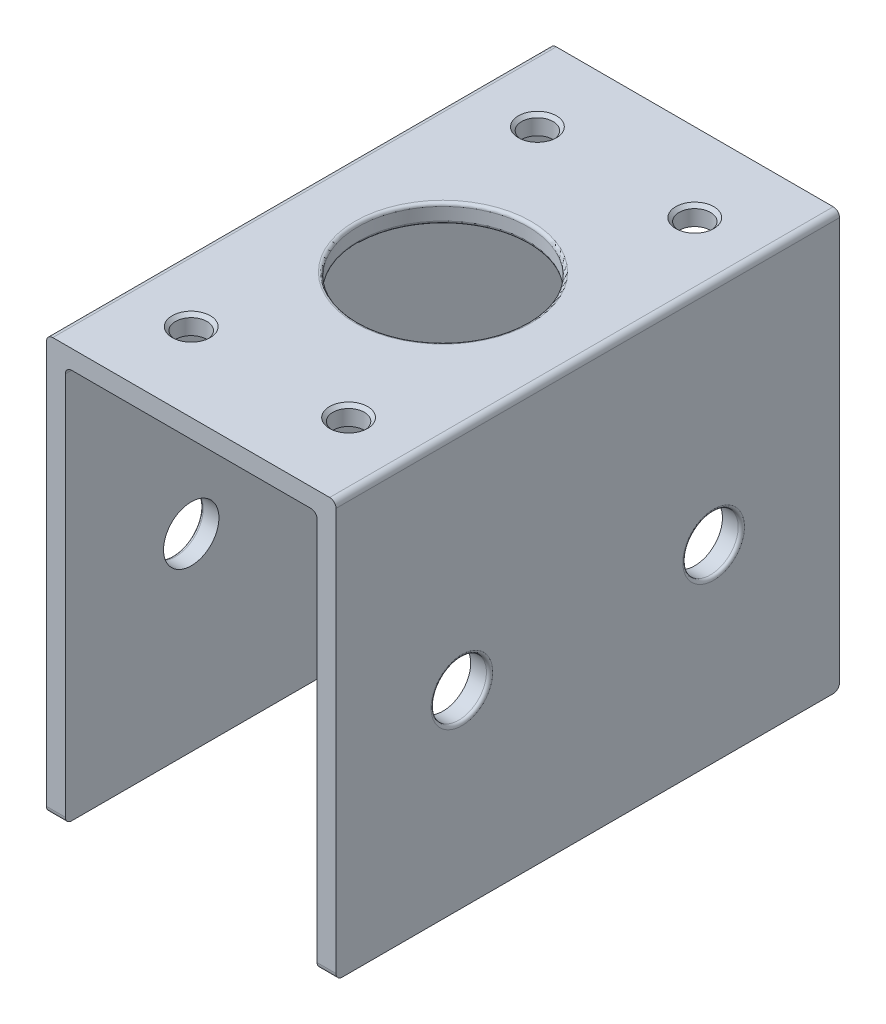
SolidWorks part; units mm, degrees
ref_plane "前视基准面" through (0, 0, 0) normal (0, 0, 1) x (1, 0, 0)
ref_plane "上视基准面" through (0, 0, 0) normal (0, 1, 0) x (1, 0, 0)
ref_plane "右视基准面" through (0, 0, 0) normal (1, 0, 0) x (0, 0, -1)
other "Configuration Table"
sketch "草图1" plane through (0, 0, 0) normal (0, 0, 1) x (1, 0, 0)
  line L0 (0, 0) -> (40, 0)
  line L1 (40, 0) -> (40, -63)
  line L2 (40, -63) -> (43, -63)
  line L3 (43, -63) -> (43, 3)
  line L4 (43, 3) -> (-3, 3)
  line L5 (-3, 3) -> (-3, -63)
  line L6 (-3, -63) -> (0, -63)
  line L7 (0, -63) -> (0, 0)
  dimension "D1" = 40
  dimension "D2" = 63
  dimension "D3" = 3
  dimension "D4" = 3
  dimension "D5" = 3
  dimension "D6" = 63
extrude "凸台-拉伸1" add sketch "草图1" along normal blind 80
sketch "草图2" plane through (0, 3, 0) normal (0, 1, 0) x (1, 0, 0)
  line L0 (43, -40) -> (-3, -40)
  line L1 (43, -80) -> (43, 0) construction
  line L2 (-3, -80) -> (-3, 0) construction
  line L3 (20, -80) -> (20, 0)
  line L4 (43, -80) -> (-3, -80) construction
  line L5 (43, 0) -> (-3, 0) construction
  line L7 (7.5, -12.5) -> (32.5, -12.5)
  line L8 (7.5, -12.5) -> (7.5, -67.5)
  line L9 (7.5, -67.5) -> (32.5, -67.5)
  line L10 (32.5, -12.5) -> (32.5, -67.5)
  line L11 (7.5, -12.5) -> (32.5, -67.5) construction
  line L12 (7.5, -67.5) -> (32.5, -12.5) construction
  circle A0 centre (32.5, -12.5) radius 2.5
  circle A1 centre (32.5, -67.5) radius 2.5
  circle A2 centre (7.5, -67.5) radius 2.5
  circle A3 centre (7.5, -12.5) radius 2.375
  point P12 (20, -40)
  dimension "D1" = 25
  dimension "D2" = 55
hole_wizard "M6 螺纹孔1" positions "草图3" profile "草图4" tap size "M6" standard "GB" end condition through all
sketch "草图3" plane through (0, 3, 0) normal (0, 1, 0) x (1, 0, 0)
  point P0 (7.5, -12.5)
  point P3 (32.5, -12.5)
  point P6 (32.5, -67.5)
  point P9 (7.5, -67.5)
sketch "草图4" plane through (7.5, 3, 12.5) normal (1, 0, 0) x (0, 0, 1)
  line L0 (0, 0) -> (0, 66)
  line L1 (0, 66) -> (2.5, 66)
  line L2 (2.5, 66) -> (2.5, 0.525)
  line L3 (2.5, 0.525) -> (3.025, 0)
  line L5 (3.025, 0) -> (0, 0)
  line L6 (-2.5, 0.525) -> (-3.025, 0) construction
  line L11 (0, -6.35) -> (0, 107.95) construction
  dimension "通孔螺纹孔钻头直径" = 5
  dimension "通孔螺纹孔钻头深度" = 66
  dimension "近端锥形沉头孔直径" = 6.05
  dimension "近端锥形沉头孔角度" = 90
cosmetic thread "孔螺蚊线1" parameters "D2"=6
cosmetic thread "孔螺蚊线2" parameters "D2"=6
cosmetic thread "孔螺蚊线3" parameters "D2"=6
cosmetic thread "孔螺蚊线4" parameters "D2"=6
sketch "草图5" plane through (0, 3, 0) normal (0, 1, 0) x (1, 0, 0)
  line L0 (43, -40) -> (-3, -40)
  line L1 (43, -80) -> (43, 0) construction
  line L2 (-3, -80) -> (-3, 0) construction
  circle A0 centre (20, -40) radius 13.5
extrude "切除-拉伸1" cut sketch "草图5" against normal blind 70 contours L0 A0 | L0 A0
sketch "草图6" plane through (43, 0, 0) normal (1, 0, 0) x (0, 0, -1)
  line L0 (-40, -63) -> (-40, -33)
  line L1 (-80, -63) -> (0, -63) construction
  line L2 (-40, -33) -> (-20, -33)
  circle A0 centre (-20, -33) radius 4.4
  circle A1 centre (-60, -33) radius 4.4
  dimension "D1" = 8.8
extrude "切除-拉伸2" cut sketch "草图6" against normal through all
fillet "圆角1" radius 1 8 edges at (41.5, -63, 0) (-1.5, -63, 0) (40, 0, 40) (0, 0, 40) (-1.5, -63, 80) (41.5, -63, 80) (43, 3, 40) (-3, 3, 40)
fillet "圆角2" radius 0.5 6 edges at (20, 0, 53.5) (6.5, 3, 40) (43, -33, 15.6) (43, -33, 55.6) (-3, -33, 55.6) (-3, -33, 15.6)
equation "\"0。5\"=10"
